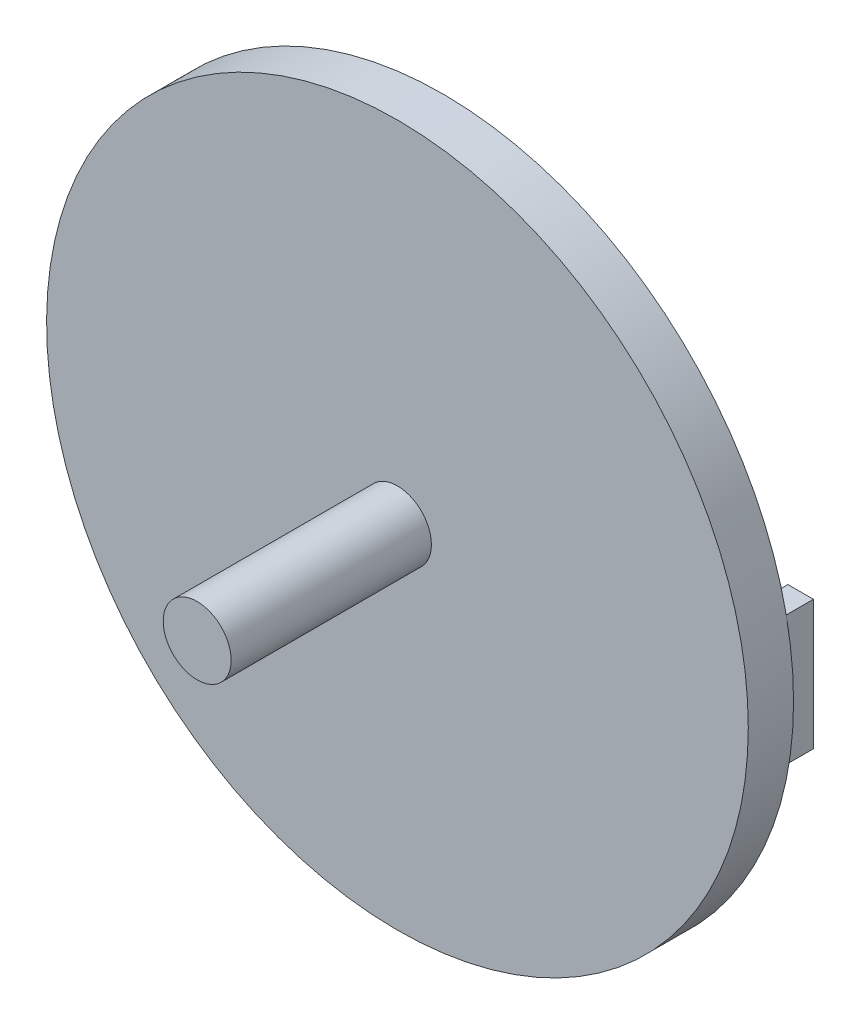
SolidWorks part; units mm, degrees
ref_plane "Front Plane" through (0, 0, 0) normal (0, 0, 1) x (1, 0, 0)
ref_plane "Top Plane" through (0, 0, 0) normal (0, 1, 0) x (1, 0, 0)
ref_plane "Right Plane" through (0, 0, 0) normal (1, 0, 0) x (0, 0, -1)
sketch "Sketch1" plane through (0, 0, 0) normal (0, 0, 1) x (1, 0, 0)
  circle A0 centre (0, 0) radius 77.5
  circle A1 centre (0, 0) radius 56.5
  circle A2 centre (0, 0) radius 7.5
  dimension "D1" = 155
  dimension "D2" = 113
  dimension "D3" = 15
extrude "Boss-Extrude1" add sketch "Sketch1" along normal blind 10 contours A0
sketch "Sketch2" plane through (0, 0, 0) normal (0, 0, -1) x (-1, 0, 0)
  circle A0 centre (0, 0) radius 56.5
  dimension "D1" = 113
extrude "Boss-Extrude2" add sketch "Sketch2" along normal blind 5.7642
sketch "Sketch3" plane through (0, 0, -5.7642) normal (0, 0, -1) x (-1, 0, 0)
  circle A1 centre (0, 0) radius 7.5
  dimension "D1" = 15
extrude "Boss-Extrude3" add sketch "Sketch3" against normal blind 60
sketch "Sketch4" plane through (0, 0, 0) normal (0, 0, -1) x (-1, 0, 0)
  line L0 (-75.8826, 15.7504) -> (-70.2466, 15.7504)
  line L1 (69.7534, 16.4567) -> (75.7326, 16.4567)
  line L2 (69.7534, 16.4567) -> (69.7534, -14.9428)
  line L3 (69.7534, -14.9428) -> (75.7326, -14.9428)
  line L4 (75.7326, 16.4567) -> (75.7326, -14.9428)
  line L5 (-75.8826, 15.7504) -> (-75.8826, -12.86)
  line L6 (-75.8826, -12.86) -> (-70.2466, -12.86)
  line L7 (-70.2466, 15.7504) -> (-70.2466, -12.86)
  circle A1 centre (0, 0) radius 77.5 construction
  point P8 (76.4594, 12.6576)
  point P10 (-68.5185, 10.8437)
  point P12 (-75.8714, 15.8043)
  point P13 (0, 0)
  point P14 (69.7534, 16.4567)
  dimension "D1" = 140
extrude "Boss-Extrude4" add sketch "Sketch4" along normal blind 6
sketch "Sketch5" plane through (0, 0, 0) normal (0, 0, 1) x (1, 0, 0)
  line L1 (-73.2782, 17.8107) -> (-65.5433, 17.8107)
  line L2 (-73.2782, 17.8107) -> (-73.2782, -19.2355)
  line L3 (-73.2782, -19.2355) -> (-65.5433, -19.2355)
  line L4 (-65.5433, 17.8107) -> (-65.5433, -19.2355)
